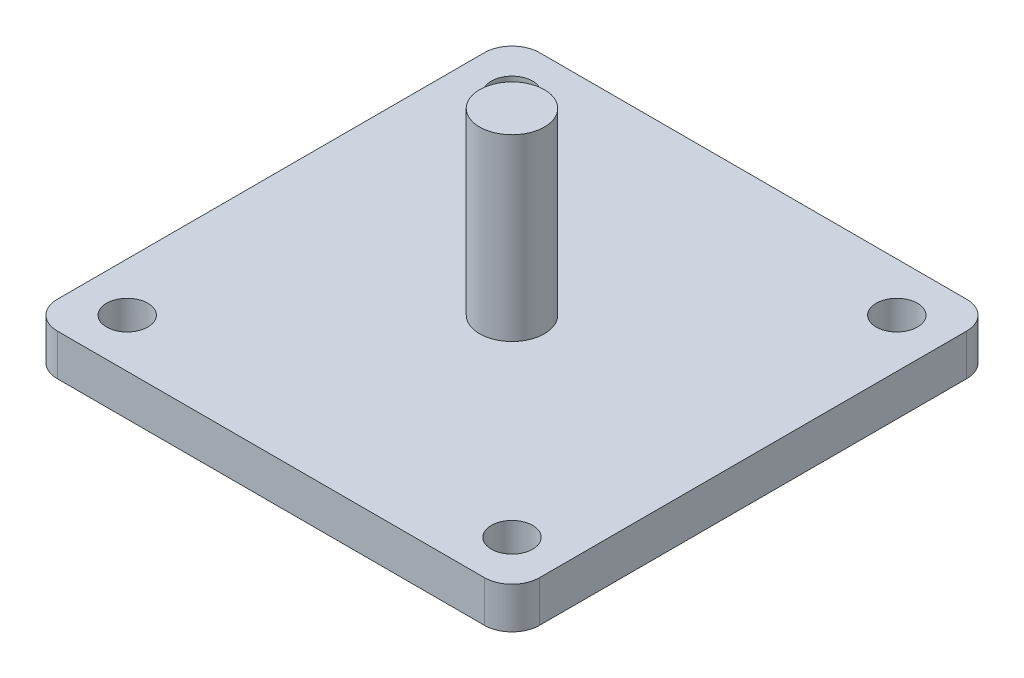
SolidWorks part; units mm, degrees
ref_plane "Plano frontal" through (0, 0, 0) normal (0, 0, 1) x (1, 0, 0)
ref_plane "Plano superior" through (0, 0, 0) normal (0, 1, 0) x (1, 0, 0)
ref_plane "Plano direito" through (0, 0, 0) normal (1, 0, 0) x (0, 0, -1)
sketch "Esboço1" plane through (0, 0, 0) normal (0, 1, 0) x (1, 0, 0)
  line L1 (-17.5, -17.5) -> (17.5, -17.5)
  line L2 (-17.5, -17.5) -> (-17.5, 17.5)
  line L3 (-17.5, 17.5) -> (17.5, 17.5)
  line L4 (17.5, -17.5) -> (17.5, 17.5)
  line L5 (-17.5, -17.5) -> (17.5, 17.5) construction
  line L6 (-17.5, 17.5) -> (17.5, -17.5) construction
  point P0 (0, 0)
  dimension "D1" = 35
  dimension "D2" = 35
extrude "Ressalto-extrusão1" add sketch "Esboço1" along normal mid plane 3
fillet "Filete1" radius 2 4 edges at (-17.5, 0, 17.5) (-17.5, 0, -17.5) (17.5, 0, -17.5) (17.5, 0, 17.5)
sketch "Esboço2" plane through (0, 1.5, 0) normal (0, 1, 0) x (1, 0, 0)
  circle A0 centre (0, 0) radius 2.35
  dimension "D1" = 4.7
extrude "Ressalto-extrusão2" add sketch "Esboço2" along normal blind 13
sketch "Esboço3" plane through (0, 1.5, 0) normal (0, 1, 0) x (1, 0, 0)
  circle A1 centre (13.9645, 13.9645) radius 1.5
  circle A6 centre (13.9645, -13.9645) radius 1.5
  circle A7 centre (-13.9645, -13.9645) radius 1.5
  circle A8 centre (-13.9645, 13.9645) radius 1.5
  point P12 (0, 0)
extrude "Corte-extrusão1" cut sketch "Esboço3" against normal blind 10
move or copy body "Corpo-Converter em corpo de malha1" [suppressed] bodies to move or copy 103 copy no translate (0, 0, 0) parameters "D1"=0, "D2"=0, "D3"=0
